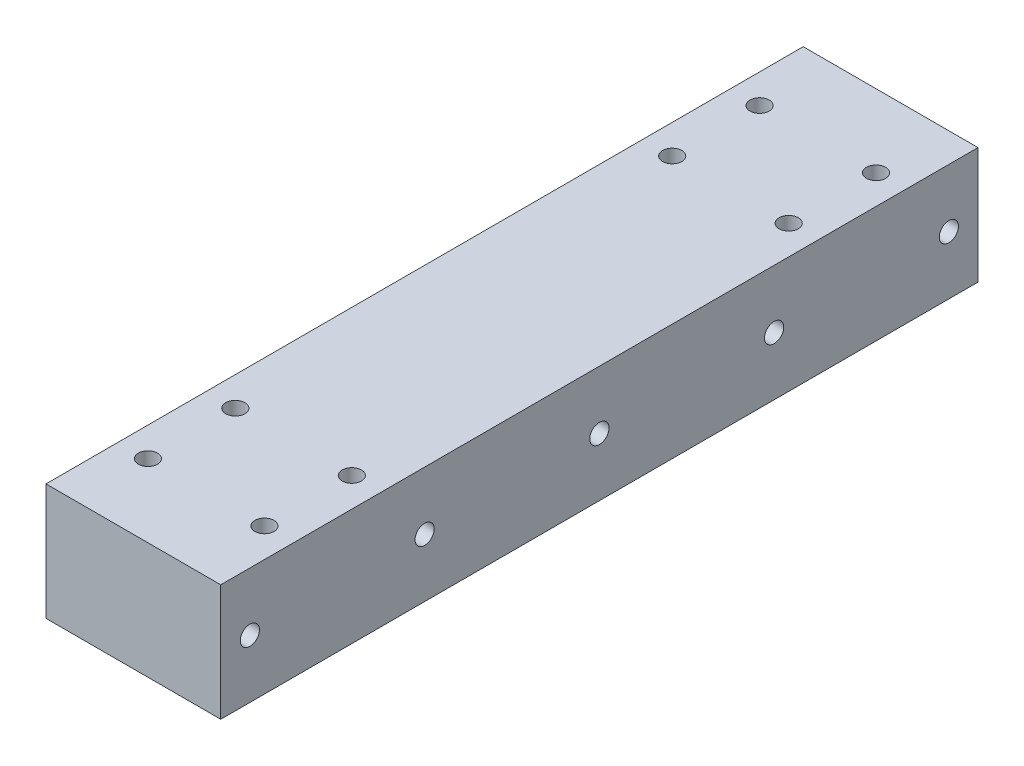
SolidWorks part; units mm, degrees
ref_plane "Front" through (0, 0, 0) normal (0, 0, 1) x (1, 0, 0)
ref_plane "Top" through (0, 0, 0) normal (0, 1, 0) x (1, 0, 0)
ref_plane "Right" through (0, 0, 0) normal (1, 0, 0) x (0, 0, -1)
sketch "Esquisse1" plane through (0, 0, 0) normal (0, 0, 1) x (1, 0, 0)
  line L1 (0, 0) -> (30, 0)
  line L2 (0, 0) -> (0, 20)
  line L3 (0, 20) -> (30, 20)
  line L4 (30, 0) -> (30, 20)
  dimension "D1" = 30
  dimension "D2" = 20
extrude "Boss.-Extru.1" add sketch "Esquisse1" along normal blind 130
sketch "Esquisse2" plane through (0, 20, 0) normal (0, 1, 0) x (1, 0, 0)
  line L0 (0, -65) -> (30, -65) construction
  line L1 (0, -130) -> (0, 0) construction
  line L2 (30, -130) -> (30, 0) construction
  line L3 (15, -130) -> (15, -65) construction
  line L4 (30, -130) -> (0, -130) construction
  line L5 (15, -110) -> (5.7001, -110) construction
  line L6 (15, -20) -> (5.7001, -20) construction
  circle A0 centre (5, -117.5) radius 1.65
  circle A1 centre (5, -102.5) radius 1.65
  circle A2 centre (25, -102.5) radius 1.65
  circle A3 centre (25, -117.5) radius 1.65
  circle A4 centre (25, -12.5) radius 1.65
  circle A5 centre (25, -27.5) radius 1.65
  circle A6 centre (5, -27.5) radius 1.65
  circle A7 centre (5, -12.5) radius 1.65
  dimension "D4" = 3.3
  dimension "D1" = 20
  dimension "D2" = 15
  dimension "D3" = 90
extrude "Enlèv. mat.-Extru.1" cut sketch "Esquisse2" against normal through all
sketch "Esquisse3" plane through (30, 0, 0) normal (1, 0, 0) x (0, 0, -1)
  line L0 (-130, 10) -> (0, 10) construction
  line L1 (-130, 0) -> (-130, 20) construction
  line L2 (0, 0) -> (0, 20) construction
  line L3 (-65, 10) -> (-65, 20) construction
  line L4 (-130, 20) -> (0, 20) construction
  circle A0 centre (-65, 10) radius 1.65
  circle A1 centre (-95, 10) radius 1.65
  circle A2 centre (-125, 10) radius 1.65
  circle A3 centre (-5, 10) radius 1.65
  circle A4 centre (-35, 10) radius 1.65
  dimension "D1" = 30
  dimension "D2" = 30
  dimension "D3" = 3.3
extrude "Enlèv. mat.-Extru.2" cut sketch "Esquisse3" against normal through all
